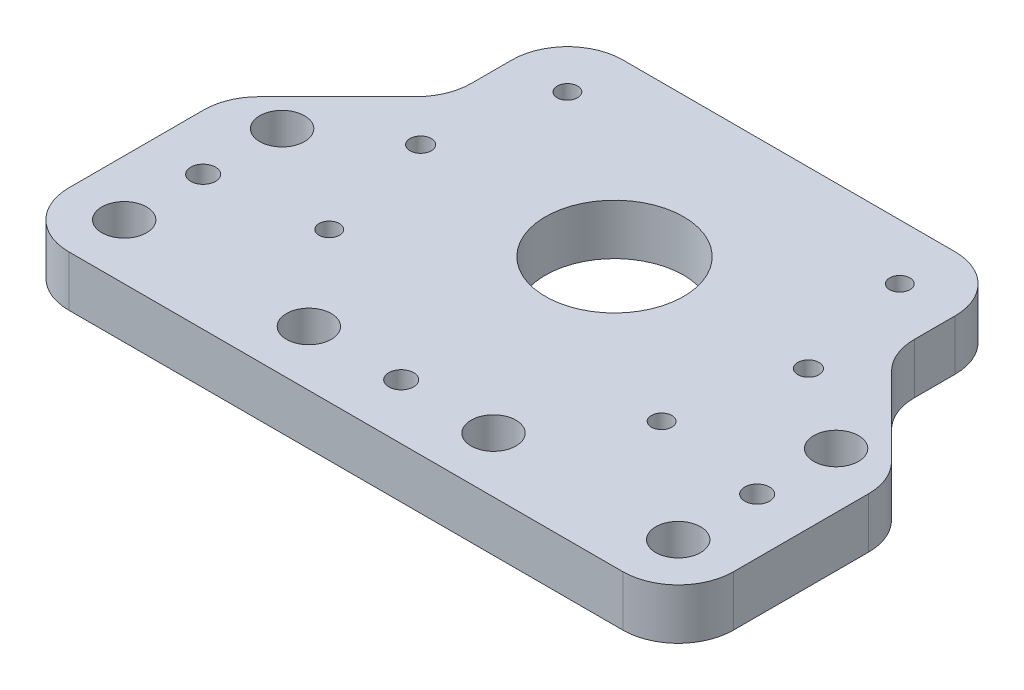
SolidWorks part; units mm, degrees
material "Balsa"
ref_plane "Front" through (0, 0, 0) normal (0, 0, 1) x (1, 0, 0)
ref_plane "Top" through (0, 0, 0) normal (0, 1, 0) x (1, 0, 0)
ref_plane "Right" through (0, 0, 0) normal (1, 0, 0) x (0, 0, -1)
sketch "Sketch1" plane through (0, 0, 0) normal (0, 1, 0) x (1, 0, 0)
  line L0 (38.1, 0) -> (38.1, 200) construction
  line L1 (0, 0) -> (76.2, 0)
  line L2 (0, 0) -> (0, 50.8)
  line L3 (0, 50.8) -> (38.1, 50.8)
  line L4 (38.1, 50.8) -> (76.2, 50.8)
  line L5 (38.1, 38.65) -> (79.051, 38.65) construction
  line L6 (38.1, 37.15) -> (79.051, 37.15) construction
  line L7 (76.2, 50.8) -> (76.2, 0)
  circle A0 centre (38.1, 118.65) radius 80 construction
  circle A1 centre (38.1, 30.8) radius 6.35 construction
  circle A2 centre (38.1, 30.8) radius 20 construction
  circle A4 centre (38.1, 30.8) radius 8
  dimension "D3" = 160
  dimension "D4" = 12.7
  dimension "D5" = 50.8
  dimension "D8" = 16
  dimension "D2" = 40
  dimension "D1" = 1.5
  dimension "D6" = 76.2
extrude "Boss-Extrude1" add sketch "Sketch1" along normal blind 5.8
sketch "Sketch2" plane through (0, 5.8, 0) normal (0, 1, 0) x (1, 0, 0)
  line L0 (38.1, 50.8) -> (38.1, 0) construction
  line L2 (0, 30.8) -> (76.2, 30.8) construction
  line L5 (76.2, 0) -> (76.2, 50.8) construction
  line L6 (76.2, 50.8) -> (0, 50.8) construction
  line L8 (0, 0) -> (76.2, 0) construction
  line L9 (0, 50.8) -> (0, 0) construction
  circle A1 centre (15.875, 30.8) radius 1.3
  circle A4 centre (60.325, 30.8) radius 1.3
  point P26 (38.1, 30.8)
  dimension "D1" = 2.6
  dimension "D2" = 22.225
extrude "Cut-Extrude1" cut sketch "Sketch2" against normal through all
sketch "Sketch14" plane through (0, 0, 0) normal (0, -1, 0) x (1, 0, 0)
  line L0 (38.1, -30.8) -> (3.391, -30.8) construction
  line L2 (38.1, -30.8) -> (38.1, -33.65) construction
  line L3 (19.05, -17.15) -> (57.15, -17.15) construction
  line L5 (57.15, -44.45) -> (19.05, -44.45) construction
  line L7 (76.2, -50.8) -> (0, -50.8) construction
  line L8 (60.325, -30.8) -> (38.1, -30.8) construction
  circle A0 centre (38.1, -30.8) radius 8 construction
  circle A1 centre (57.15, -44.45) radius 1.25
  circle A2 centre (19.05, -44.45) radius 1.25
  circle A3 centre (19.05, -17.15) radius 1.25
  circle A4 centre (57.15, -17.15) radius 1.25
  circle A5 centre (60.325, -30.8) radius 1.3 construction
  point P0 (57.15, -44.45)
  point P12 (19.05, -44.45)
  point P13 (19.05, -17.15)
  point P14 (57.15, -17.15)
  dimension "D3" = 2.5
  dimension "D1" = 19.05
  dimension "D2" = 6.35
extrude "M3-tap" cut sketch "Sketch14" against normal through all
sketch "Sketch15" plane through (0, 0, 0) normal (0, -1, 0) x (1, 0, 0)
  line L0 (38.1, 0) -> (38.1, -48.7422) construction
  line L2 (76.2, 0) -> (76.2, -50.8) construction
  line L3 (0, 0) -> (76.2, 0) construction
  line L5 (76.2, -24.45) -> (69.85, -24.45) construction
  line L10 (69.85, -24.45) -> (69.85, 0) construction
  line L14 (69.85, -6.35) -> (48.6833, -6.35) construction
  line L15 (48.6833, -6.35) -> (27.5167, -6.35) construction
  line L16 (27.5167, -6.35) -> (6.35, -6.35) construction
  circle A0 centre (69.85, -24.45) radius 2.65
  circle A1 centre (69.85, -6.35) radius 2.65
  circle A2 centre (48.6833, -6.35) radius 2.65
  circle A3 centre (27.5167, -6.35) radius 2.65
  circle A4 centre (6.35, -6.35) radius 2.65
  circle A5 centre (6.35, -24.45) radius 2.65
  point P0 (69.85, -24.45)
  point P1 (69.85, -6.35)
  point P35 (6.35, -6.35)
  point P36 (6.35, -24.45)
  point P42 (48.6833, -6.35)
  point P50 (27.5167, -6.35)
  dimension "D4" = 5.3
  dimension "D1" = 6.35
  dimension "D2" = 6.35
  dimension "D3" = 24.45
extrude "M5-through" cut sketch "Sketch15" against normal through all
sketch "Sketch12" plane through (0, 5.8, 0) normal (0, 1, 0) x (1, 0, 0)
  line L1 (0, 50.8) -> (12.7, 50.8)
  line L2 (0, 50.8) -> (0, 24.45)
  line L4 (12.7, 50.8) -> (12.7, 37.15)
  line L5 (38.1, 30.8) -> (38.1, 50.8) construction
  line L6 (76.2, 50.8) -> (0, 50.8) construction
  line L7 (63.5, 50.8) -> (63.5, 37.15)
  line L8 (76.2, 24.45) -> (63.5, 37.15)
  line L9 (76.2, 50.8) -> (76.2, 24.45)
  line L10 (76.2, 50.8) -> (63.5, 50.8)
  line L11 (12.7, 37.15) -> (0, 24.45)
  line L12 (0, 50.8) -> (0, 0) construction
  circle A1 centre (19.05, 44.45) radius 1.25 construction
  dimension "D1" = 6.35
  dimension "D2" = 13.65
  dimension "D3" = 45
extrude "Cut-Extrude2" cut sketch "Sketch12" against normal through all
fillet "Fillet2" radius 6.35 8 edges at (76.2, 2.9, 0) (0, 2.9, 0) (76.2, 2.9, -24.45) (63.5, 2.9, -37.15) (63.5, 2.9, -50.8) (12.7, 2.9, -50.8) (0, 2.9, -24.45) (12.7, 2.9, -37.15)
sketch "Sketch13" plane through (0, 0, 0) normal (0, -1, 0) x (1, 0, 0)
  line L0 (69.85, -24.45) -> (69.85, -6.35) construction
  line L1 (69.85, -6.35) -> (6.35, -6.35) construction
  line L2 (6.35, -6.35) -> (6.35, -24.45) construction
  circle A0 centre (69.85, -15.4) radius 1.5
  circle A1 centre (38.1, -6.35) radius 1.5
  circle A2 centre (6.35, -15.4) radius 1.5
  dimension "D1" = 3
extrude "Cut-Extrude3" cut sketch "Sketch13" against normal through all
other "Move Face1" face at (38.1, 5.8, -22.8) face at (15.875, 0, -29.5) face at (60.325, 0, -32.1) face at (57.15, 5.8, -45.7) face at (19.05, 5.8, -45.7) face at (19.05, 5.8, -18.4) face at (57.15, 5.8, -18.4) face at (69.85, 5.8, -27.1) face at (69.85, 5.8, -9) face at (48.6833, 5.8, -9) face at (27.5167, 5.8, -9) face at (6.35, 5.8, -9) face at (6.35, 5.8, -27.1) face at (69.85, 5.8, -16.9) face at (38.1, 5.8, -7.85) face at (6.35, 5.8, -16.9) parameters "D1"=0.08
